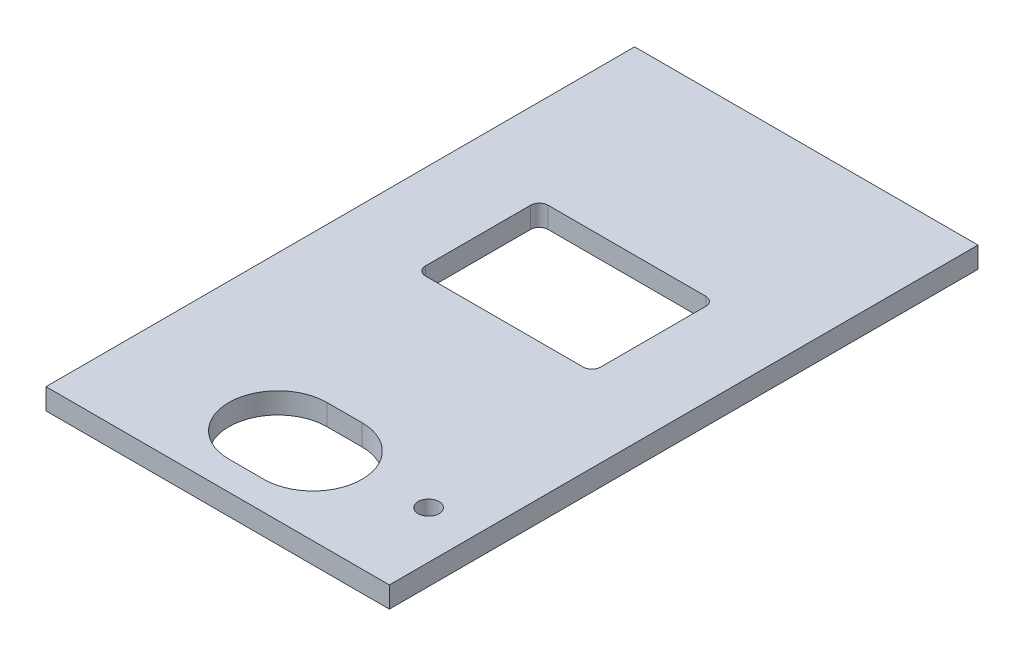
SolidWorks part; units mm, degrees
ref_plane "Front Plane" through (0, 0, 0) normal (0, 0, 1) x (1, 0, 0)
ref_plane "Top Plane" through (0, 0, 0) normal (0, 1, 0) x (1, 0, 0)
ref_plane "Right Plane" through (0, 0, 0) normal (1, 0, 0) x (0, 0, -1)
sketch "Sketch1" plane through (0, 0, 0) normal (0, 1, 0) x (1, 0, 0)
  line L1 (98, -168) -> (-98, -168)
  line L2 (98, -168) -> (98, 168)
  line L3 (98, 168) -> (-98, 168)
  line L4 (-98, -168) -> (-98, 168)
  line L5 (98, -168) -> (-98, 168) construction
  line L6 (98, 168) -> (-98, -168) construction
  point P0 (0, 0)
  dimension "D1" = 196
  dimension "D2" = 336
extrude "Boss-Extrude2" add sketch "Sketch1" along normal blind 12
sketch "Sketch3" plane through (0, 12, 0) normal (0, 1, 0) x (1, 0, 0)
  line L1 (86, -158.6126) -> (-86, -158.6126)
  line L2 (86, -158.6126) -> (86, 158.6126)
  line L3 (86, 158.6126) -> (-86, 158.6126)
  line L4 (-86, -158.6126) -> (-86, 158.6126)
  line L5 (86, -158.6126) -> (-86, 158.6126) construction
  line L6 (86, 158.6126) -> (-86, -158.6126) construction
  point P0 (0, 0)
  dimension "D1" = 172
  dimension "D2" = 317.2252
sketch "Sketch5" plane through (0, 12, 0) normal (0, 1, 0) x (1, 0, 0)
  line L0 (0, -93.6126) -> (0, -95.6126) construction
  line L1 (86, -158.6126) -> (-86, -158.6126) construction
  line L2 (86, 158.6126) -> (-86, 158.6126) construction
  line L9 (10, -151.6126) -> (-10, -151.6126)
  line L11 (10, -95.6126) -> (-10, -95.6126)
  line L17 (0, -151.6126) -> (0, -158.6126) construction
  arc A0 (-10, -95.6126) -> (-10, -151.6126) centre (-10, -123.6126) ccw
  arc A3 (10, -151.6126) -> (10, -95.6126) centre (10, -123.6126) ccw
  point P5 (0, -123.6126)
  point P10 (0, -123.6126)
  dimension "D1" = 282.2252
  dimension "D3" = 35
  dimension "D4" = 20
  dimension "D5" = 56
extrude "Cut-Extrude1" cut sketch "Sketch5" against normal blind 12
sketch "Sketch6" plane through (0, 12, 0) normal (0, 1, 0) x (1, 0, 0)
  line L1 (45.6061, -5) -> (-44.3939, -5)
  line L2 (50.6061, 0) -> (50.6061, 60)
  line L3 (45.6061, 65) -> (-44.3939, 65)
  line L4 (-49.3939, 0) -> (-49.3939, 60)
  line L5 (50.6061, -5) -> (-49.3939, 65) construction
  line L6 (50.6061, 65) -> (-49.3939, -5) construction
  arc A0 (-44.3939, -5) -> (-49.3939, 0) centre (-44.3939, 0) cw
  arc A1 (45.6061, -5) -> (50.6061, 0) centre (45.6061, 0) ccw
  arc A2 (50.6061, 60) -> (45.6061, 65) centre (45.6061, 60) ccw
  arc A3 (-44.3939, 65) -> (-49.3939, 60) centre (-44.3939, 60) ccw
  point P0 (0.6061, 30)
  dimension "D4" = 5
  dimension "D1" = 100
  dimension "D2" = 70
  dimension "D3" = 30
extrude "Cut-Extrude2" cut sketch "Sketch6" against normal blind 12
sketch "Sketch7" plane through (0, 12, 0) normal (0, 1, 0) x (1, 0, 0)
  line L0 (86, -158.6126) -> (86, 158.6126) construction
  line L1 (86, -158.6126) -> (-86, -158.6126) construction
  circle A0 centre (71, -118.6126) radius 6
  dimension "D1" = 12
  dimension "D2" = 15
  dimension "D3" = 40
extrude "Cut-Extrude3" cut sketch "Sketch7" against normal blind 73
